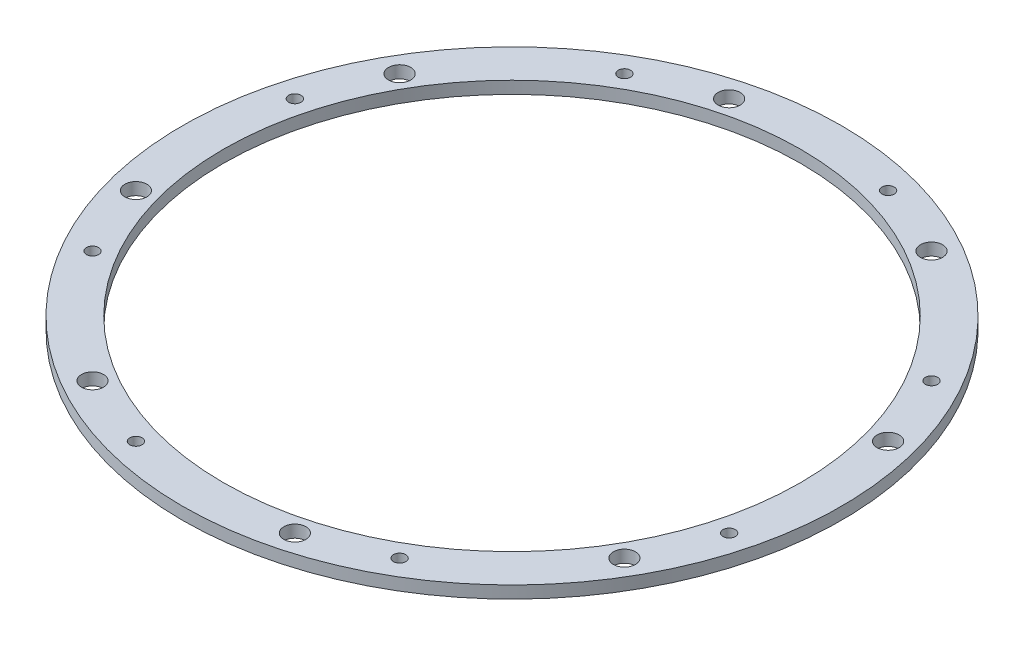
SolidWorks part; units mm, degrees
material "Nylon 101"
ref_plane "Front Plane" through (0, 0, 0) normal (0, 0, 1) x (1, 0, 0)
ref_plane "Top Plane" through (0, 0, 0) normal (0, 1, 0) x (1, 0, 0)
ref_plane "Right Plane" through (0, 0, 0) normal (1, 0, 0) x (0, 0, -1)
sketch "Sketch1" plane through (0, 0, 0) normal (0, 1, 0) x (1, 0, 0)
  line L0 (100.17, 0) -> (0, 0) construction
  line L1 (0, 0) -> (86.7498, 50.085) construction
  circle A0 centre (0, 0) radius 94.17
  circle A1 centre (0, 0) radius 107.5
  circle A2 centre (0, 0) radius 100.17 construction
  circle A3 centre (86.7498, 50.085) radius 2
  circle A4 centre (96.7568, -25.9259) radius 2
  circle A5 centre (50.085, -86.7498) radius 2
  circle A6 centre (-25.9259, -96.7568) radius 2
  circle A7 centre (-86.7498, -50.085) radius 2
  circle A8 centre (-96.7568, 25.9259) radius 2
  circle A9 centre (-50.085, 86.7498) radius 2
  circle A10 centre (25.9259, 96.7568) radius 2
  point P24 (0, 0)
  dimension "D1" = 188.34
  dimension "D2" = 200.34
  dimension "D3" = 215
  dimension "D5" = 4
  dimension "D4" = 30
  dimension "D6" = 8
extrude "Boss-Extrude1" add sketch "Sketch1" along normal blind 4
sketch "Sketch2" plane through (0, 4, 0) normal (0, 1, 0) x (1, 0, 0)
  line L0 (107.5, 0) -> (0, 0) construction
  line L1 (0, 0) -> (96.7568, 25.9259) construction
  circle A0 centre (0, 0) radius 107.5 construction
  circle A1 centre (0, 0) radius 100.17 construction
  circle A2 centre (96.7568, 25.9259) radius 3.6
  circle A3 centre (86.7498, -50.085) radius 3.6
  circle A4 centre (25.9259, -96.7568) radius 3.6
  circle A5 centre (-50.085, -86.7498) radius 3.6
  circle A6 centre (-96.7568, -25.9259) radius 3.6
  circle A7 centre (-86.7498, 50.085) radius 3.6
  circle A8 centre (-25.9259, 96.7568) radius 3.6
  circle A9 centre (50.085, 86.7498) radius 3.6
  point P8 (36.6863, 83.4222)
  point P9 (0, 0)
  point P24 (0, 0)
  dimension "D1" = 200.34
  dimension "D3" = 7.2
  dimension "D2" = 15
  dimension "D4" = 8
extrude "Cut-Extrude1" cut sketch "Sketch2" against normal blind 10
